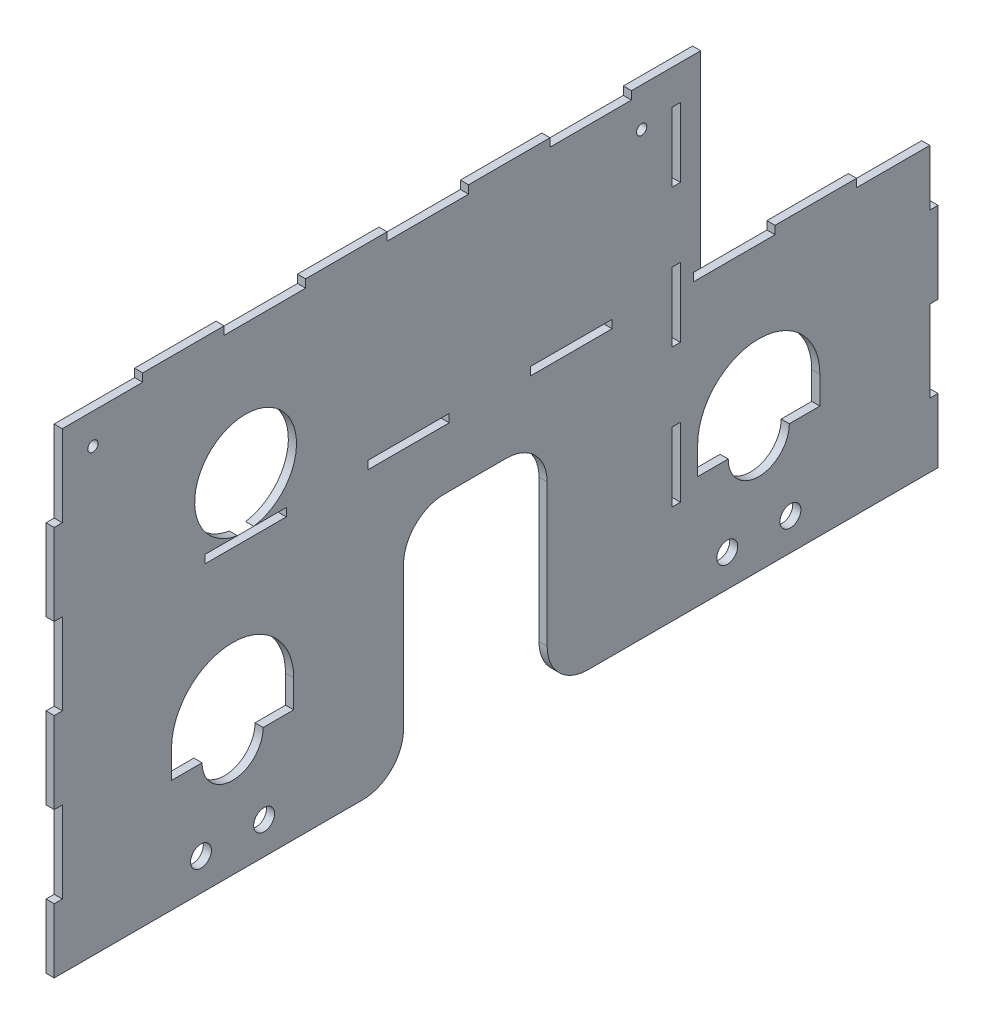
SolidWorks part; units mm, degrees
ref_plane "Front Plane" through (0, 0, 0) normal (0, 0, 1) x (1, 0, 0)
ref_plane "Top Plane" through (0, 0, 0) normal (0, 1, 0) x (1, 0, 0)
ref_plane "Right Plane" through (0, 0, 0) normal (1, 0, 0) x (0, 0, -1)
sketch "Sketch1" plane through (0, 0, 0) normal (1, 0, 0) x (0, 0, -1)
  line L1 (-112.2312, 74.803) -> (112.2312, 74.803)
  line L2 (-112.2312, 74.803) -> (-112.2312, -74.803)
  line L3 (-112.2312, -74.803) -> (112.2312, -74.803)
  line L4 (112.2312, 74.803) -> (112.2312, -74.803)
  line L5 (0, -74.803) -> (0, 74.803) construction
  line L6 (-112.2312, 0) -> (112.2312, 0) construction
  point P0 (0, 0)
  dimension "D1" = 224.4623
  dimension "D2" = 149.606
extrude "Boss-Extrude1" add sketch "Sketch1" along normal blind 2.54
sketch "Sketch2" plane through (2.54, 0, 0) normal (1, 0, 0) x (0, 0, -1)
  line L0 (-112.2312, -74.803) -> (112.2312, -74.803) construction
  line L1 (112.2312, 74.803) -> (67.7812, 74.803)
  line L2 (112.2312, 74.803) -> (112.2312, -12.7381)
  line L3 (112.2312, -12.7381) -> (67.7812, -12.7381)
  line L4 (67.7812, 74.803) -> (67.7812, -12.7381)
  dimension "D1" = 44.45
  dimension "D2" = 62.0649
extrude "Cut-Extrude1" cut sketch "Sketch2" against normal through all
fillet "Fillet1" [suppressed] radius 20.0025
hole_wizard "1/4 Clearance Hole1" positions "Sketch3" profile "Sketch5" hole size "1/4" standard "ANSI Inch"
sketch "Sketch3" plane through (2.54, 0, 0) normal (1, 0, 0) x (0, 0, -1)
  line L0 (-112.2312, -74.803) -> (112.2312, -74.803) construction
  line L3 (82.4116, -64.77) -> (102.0966, -64.77) construction
  line L6 (112.2312, -74.803) -> (112.2312, -12.7381) construction
  point P0 (-81.6978, -64.77)
  point P2 (-62.0128, -64.77)
  point P4 (102.0966, -64.77)
  point P6 (82.4116, -64.77)
  dimension "D1" = 10.033
  dimension "D2" = 19.685
  dimension "D3" = 19.685
  dimension "D4" = 144.4244
  dimension "D5" = 10.1346
sketch "Sketch5" plane through (2.54, -64.77, 81.6978) normal (0, 1, 0) x (0, 0, -1)
  line L0 (0, 0) -> (0, 11.3591)
  line L1 (0, 11.3591) -> (3.2639, 9.398)
  line L2 (3.2639, 9.398) -> (3.2639, 0)
  line L5 (3.2639, 0) -> (0, 0)
  line L10 (0, 11.3591) -> (-3.2639, 9.398) construction
  line L11 (0, -6.35) -> (0, 107.95) construction
  dimension "Hole Dia." = 6.5278
  dimension "Hole Depth" = 9.398
  dimension "Drill Angle" = 118
sketch "Sketch6" plane through (2.54, 0, 0) normal (1, 0, 0) x (0, 0, -1)
  line L0 (67.7812, 74.803) -> (-112.2312, 74.803) construction
  line L1 (52.5412, 74.803) -> (27.1412, 74.803)
  line L2 (52.5412, 74.803) -> (52.5412, 72.263)
  line L3 (52.5412, 72.263) -> (27.1412, 72.263)
  line L4 (27.1412, 74.803) -> (27.1412, 72.263)
  line L7 (67.7812, 74.803) -> (67.7812, -12.7381) construction
  dimension "D1" = 2.54
  dimension "D2" = 25.4
  dimension "D3" = 15.24
extrude "Cut-Extrude2" cut sketch "Sketch6" against normal through all
pattern_linear "LPattern1" count 4 spacing 50.8 along (0, 0, 1) of "Cut-Extrude2"
sketch "Sketch7" plane through (2.54, 0, 0) normal (1, 0, 0) x (0, 0, -1)
  line L0 (67.7812, 74.803) -> (67.7812, -12.7381) construction
  line L1 (67.7812, 64.008) -> (65.2412, 64.008)
  line L2 (67.7812, 64.008) -> (67.7812, 42.418)
  line L3 (67.7812, 42.418) -> (65.2412, 42.418)
  line L4 (65.2412, 64.008) -> (65.2412, 42.418)
  line L5 (67.7812, 74.803) -> (52.5412, 74.803) construction
  dimension "D1" = 2.54
  dimension "D2" = 21.59
  dimension "D3" = 10.795
extrude "Cut-Extrude3" cut sketch "Sketch7" against normal through all
pattern_linear "LPattern2" count 3 spacing 43.18 along (0, -1, 0) of "Cut-Extrude3"
sketch "Sketch8" plane through (2.54, 0, 0) normal (1, 0, 0) x (0, 0, -1)
  line L0 (112.2312, -74.803) -> (112.2312, -12.7381) construction
  line L1 (-112.2312, -74.803) -> (112.2312, -74.803) construction
  circle A0 centre (92.2287, -39.737) radius 9.525
  circle A1 centre (-71.8299, -39.737) radius 9.525
  dimension "D1" = 20.0025
  dimension "D2" = 35.066
  dimension "D3" = 19.05
  dimension "D4" = 164.0586
extrude "Cut-Extrude4" cut sketch "Sketch8" against normal through all
sketch "Sketch9" plane through (2.54, 0, 0) normal (1, 0, 0) x (0, 0, -1)
  line L1 (-18.5407, -74.803) -> (26.2395, -74.803)
  line L2 (-18.5407, -74.803) -> (-18.5407, -4.953)
  line L3 (-18.5407, -4.953) -> (26.2395, -4.953)
  line L4 (26.2395, -74.803) -> (26.2395, -4.953)
  line L5 (-112.2312, 72.263) -> (-112.2312, -74.803) construction
  line L6 (-112.2312, -74.803) -> (112.2312, -74.803) construction
  line L7 (-112.2312, 72.263) -> (-99.8588, 72.263) construction
  circle A0 centre (-67.7863, 31.7373) radius 15.875
  dimension "D5" = 44.4449
  dimension "D6" = 31.75
  dimension "D1" = 69.85
  dimension "D2" = 44.7802
  dimension "D3" = 93.6904
  dimension "D7" = 40.5257
extrude "Cut-Extrude5" cut sketch "Sketch9" against normal through all
fillet "Fillet2" radius 12.7 4 edges at (1.27, -4.953, -26.2395) (1.27, -4.953, 18.5407) (1.27, -74.803, -26.2395) (1.27, -74.803, 18.5407)
hole_wizard "Tap Drill for M2x0.4 Tap1" [suppressed] positions "Sketch10" profile "Sketch11" hole size "M2x0.4" standard "ANSI Metric"
sketch "Sketch10" plane through (2.54, 0, 0) normal (1, 0, 0) x (0, 0, -1)
  point P0 (-47.84, 62.1794)
  point P2 (-47.84, 13.1794)
  point P4 (10.16, 13.1794)
  point P6 (10.16, 62.1794)
  dimension "D1" = 58
  dimension "D2" = 49
  dimension "D3" = 10.16
  dimension "D4" = 13.1794
sketch "Sketch11" plane through (2.54, 62.1794, 47.84) normal (0, 1, 0) x (0, 0, -1)
  line L0 (0, 0) -> (0, 2.54)
  line L1 (0, 2.54) -> (0.8, 2.54)
  line L2 (0.8, 2.54) -> (0.8, 0)
  line L5 (0.8, 0) -> (0, 0)
  line L11 (0, -6.35) -> (0, 107.95) construction
  dimension "Thru Hole Dia." = 1.6
  dimension "Thru Hole Depth" = 2.54
sketch "Sketch12" [suppressed] plane through (2.54, 0, 0) normal (1, 0, 0) x (0, 0, -1)
  line L2 (-3.3388, -5.715) -> (60.1612, -5.715)
  line L10 (60.1612, -26.035) -> (60.1612, -5.715)
  line L12 (-3.3388, -5.715) -> (-3.3388, -26.035)
  line L14 (60.1612, -26.035) -> (-3.3388, -26.035)
  line L15 (67.7812, -0.762) -> (67.7812, -12.7381) construction
  line L16 (-112.2312, -74.803) -> (112.2312, -74.803) construction
  dimension "D1" = 7.62
  dimension "D2" = 63.5
  dimension "D3" = 48.768
  dimension "D5" = 20.32
extrude "Cut-Extrude6" [suppressed] cut sketch "Sketch12" against normal through all
fillet "Fillet3" [suppressed] radius 12.7
fillet "Fillet4" [suppressed] radius 5.08
sketch "Sketch25" plane through (2.54, 0, 0) normal (1, 0, 0) x (0, 0, -1)
  line L0 (-112.2312, -74.803) -> (-31.2407, -74.803) construction
  line L1 (-112.2312, 72.263) -> (-124.9312, 72.263)
  line L2 (-112.2312, 72.263) -> (-112.2312, -74.803)
  line L3 (-112.2312, -74.803) -> (-124.9312, -74.803)
  line L4 (-124.9312, 72.263) -> (-124.9312, -74.803)
  dimension "D1" = 12.7
extrude "Boss-Extrude5" add sketch "Sketch25" against normal blind 2.54
sketch "Sketch16" plane through (2.54, 0, 0) normal (1, 0, 0) x (0, 0, -1)
  line L1 (-124.9312, 46.863) -> (-127.4712, 46.863)
  line L2 (-124.9312, 46.863) -> (-124.9312, 21.463)
  line L3 (-124.9312, 21.463) -> (-127.4712, 21.463)
  line L4 (-127.4712, 46.863) -> (-127.4712, 21.463)
  line L5 (-124.9312, 72.263) -> (-99.8588, 72.263) construction
  line L6 (-124.9312, 72.263) -> (-124.9312, -74.803) construction
  dimension "D1" = 2.54
  dimension "D2" = 25.4
  dimension "D3" = 25.4
extrude "Boss-Extrude2" add sketch "Sketch16" against normal blind 2.54
sketch "Sketch23" plane through (2.54, 0, 0) normal (1, 0, 0) x (0, 0, -1)
  line L1 (112.2312, -12.7381) -> (67.7812, -12.7381)
  line L2 (112.2312, -12.7381) -> (112.2312, 74.803)
  line L3 (112.2312, 74.803) -> (67.7812, 74.803)
  line L4 (67.7812, -12.7381) -> (67.7812, 74.803)
extrude "Boss-Extrude3" add sketch "Sketch23" against normal blind 2.54
sketch "Sketch24" plane through (2.54, 0, 0) normal (1, 0, 0) x (0, 0, -1)
  line L0 (112.2312, 74.803) -> (52.5412, 74.803) construction
  line L1 (112.2312, -74.803) -> (145.5687, -74.803)
  line L2 (112.2312, -74.803) -> (112.2312, 74.803)
  line L3 (112.2312, 74.803) -> (145.5687, 74.803)
  line L4 (145.5687, -74.803) -> (145.5687, 74.803)
  dimension "D1" = 33.3375
extrude "Boss-Extrude4" add sketch "Sketch24" against normal blind 2.54
pattern_linear "LPattern3" count 3 spacing 50.8 along (0, -1, 0) count 2 spacing 273.0398 along (0, 0, -1) of "Boss-Extrude2"
sketch "Sketch18" plane through (2.54, 0, 0) normal (1, 0, 0) x (0, 0, -1)
  line L6 (148.1087, -80.137) -> (148.1087, -54.737) construction
  line L7 (-127.4712, -80.137) -> (148.1087, -80.137)
  line L8 (-127.4712, -80.137) -> (-127.4712, -74.803)
  line L9 (-127.4712, -74.803) -> (148.1087, -74.803)
  line L10 (148.1087, -80.137) -> (148.1087, -74.803)
  line L11 (-124.9312, -74.803) -> (-31.2407, -74.803) construction
extrude "Cut-Extrude7" cut sketch "Sketch18" against normal through all
hole_wizard "M3 Clearance Hole1" positions "Sketch13" profile "Sketch14" hole size "M3" standard "ANSI Metric"
sketch "Sketch13" plane through (2.54, 0, 0) normal (1, 0, 0) x (0, 0, -1)
  line L1 (-124.9312, 72.263) -> (-99.8588, 72.263) construction
  line L2 (65.2412, 64.008) -> (65.2412, 42.418) construction
  line L3 (27.1412, 72.263) -> (52.5412, 72.263) construction
  line L4 (-124.9312, 72.263) -> (-124.9312, 46.863) construction
  point P0 (-115.4062, 62.738)
  point P2 (55.7162, 62.738)
  dimension "D1" = 9.525
  dimension "D2" = 9.525
  dimension "D3" = 9.525
  dimension "D4" = 9.525
sketch "Sketch14" plane through (2.54, 62.738, 115.4062) normal (0, 1, 0) x (0, 0, -1)
  line L0 (0, 0) -> (0, 10.3594)
  line L1 (0, 10.3594) -> (1.6, 9.398)
  line L2 (1.6, 9.398) -> (1.6, 0)
  line L5 (1.6, 0) -> (0, 0)
  line L10 (0, 10.3594) -> (-1.6, 9.398) construction
  line L11 (0, -6.35) -> (0, 107.95) construction
  dimension "Hole Dia." = 3.2
  dimension "Hole Depth" = 9.398
  dimension "Drill Angle" = 118
hole_wizard "Tap Drill for M2x0.4 Tap2" [suppressed] positions "Sketch19" profile "Sketch20" hole size "M2x0.4" standard "ANSI Metric"
sketch "Sketch19" plane through (2.54, 0, 0) normal (1, 0, 0) x (0, 0, -1)
  point P0 (35.8912, 53.1572)
  point P2 (56.8912, 53.1572)
  point P4 (56.8912, 40.6572)
  point P6 (35.8912, 40.6572)
  dimension "D1" = 21
  dimension "D2" = 12.5
  dimension "D3" = 35.8912
  dimension "D4" = 53.1572
sketch "Sketch20" plane through (2.54, 53.1572, -35.8912) normal (0, 1, 0) x (0, 0, -1)
  line L0 (0, 0) -> (0, 2.54)
  line L1 (0, 2.54) -> (0.8, 2.54)
  line L2 (0.8, 2.54) -> (0.8, 0)
  line L5 (0.8, 0) -> (0, 0)
  line L11 (0, -6.35) -> (0, 107.95) construction
  dimension "Thru Hole Dia." = 1.6
  dimension "Thru Hole Depth" = 2.54
sketch "Sketch21" [suppressed] plane through (2.54, 0, 0) normal (1, 0, 0) x (0, 0, -1)
  circle A0 centre (46.3912, 40.6072) radius 6.985
  dimension "D1" = 46.3912
  dimension "D3" = 13.97
  dimension "D2" = 40.6072
extrude "Cut-Extrude8" [suppressed] cut sketch "Sketch21" against normal through all
ref_plane "Plane1" through (2.54, 74.803, -52.5412) normal (0, 0, 1) x (1, 0, 0)
sketch "Sketch27" plane through (2.54, 0, 0) normal (1, 0, 0) x (0, 0, -1)
  line L0 (145.5687, 74.803) -> (52.5412, 74.803) construction
  line L1 (74.1312, 74.803) -> (148.1087, 74.803)
  line L2 (74.1312, 74.803) -> (74.1312, 16.0655)
  line L3 (74.1312, 16.0655) -> (148.1087, 16.0655)
  line L4 (148.1087, 74.803) -> (148.1087, 16.0655)
  line L5 (148.1087, 21.463) -> (148.1087, 46.863) construction
  line L7 (67.7812, 64.008) -> (67.7812, 42.418) construction
  dimension "D1" = 58.7375
  dimension "D2" = 6.35
extrude "Cut-Extrude9" cut sketch "Sketch27" against normal blind 2.54
sketch "Sketch28" plane through (0, 0, 0) normal (-1, 0, 0) x (0, 0, 1)
  line L0 (-92.2287, -39.737) -> (-92.2287, -49.262) construction
  line L2 (-111.2787, -31.101) -> (-111.2787, -39.737)
  line L3 (-111.2787, -39.737) -> (-73.1787, -39.737)
  line L4 (-73.1787, -31.101) -> (-73.1787, -39.737)
  line L5 (71.8299, -39.737) -> (71.8299, -49.262) construction
  line L7 (52.7799, -31.101) -> (52.7799, -39.737)
  line L8 (52.7799, -39.737) -> (90.8799, -39.737)
  line L9 (90.8799, -31.101) -> (90.8799, -39.737)
  circle A0 centre (71.8299, -39.737) radius 9.525 construction
  circle A1 centre (-92.2287, -39.737) radius 9.525 construction
  arc A2 (-111.2787, -31.101) -> (-73.1787, -31.101) centre (-92.2287, -31.101) cw
  arc A3 (52.7799, -31.101) -> (90.8799, -31.101) centre (71.8299, -31.101) cw
  point P20 (71.8299, -39.737)
  dimension "D1" = 38.1
  dimension "D2" = 8.636
  dimension "D3" = 38.1
extrude "Cut-Extrude10" cut sketch "Sketch28" against normal blind 2.54
sketch "Sketch29" plane through (2.54, 0, 0) normal (1, 0, 0) x (0, 0, -1)
  line L0 (145.5687, -3.937) -> (145.5687, 16.0655) construction
  line L1 (148.1087, 16.0655) -> (122.7087, 16.0655)
  line L2 (148.1087, 16.0655) -> (148.1087, 13.5255)
  line L3 (148.1087, 13.5255) -> (122.7087, 13.5255)
  line L4 (122.7087, 16.0655) -> (122.7087, 13.5255)
  line L5 (74.1312, 16.0655) -> (145.5687, 16.0655) construction
  dimension "D1" = 25.4
  dimension "D2" = 2.54
  dimension "D3" = 2.54
extrude "Cut-Extrude11" cut sketch "Sketch29" against normal through all
pattern_linear "LPattern4" count 5 spacing 50.8 along (0, 0, 1) of "Cut-Extrude11"
sketch "Sketch30" [suppressed] plane through (2.54, 0, 0) normal (1, 0, 0) x (0, 0, -1)
  line L0 (-47.84, 57.0994) -> (-47.84, 22.8314) construction
  line L1 (-46.57, 57.0994) -> (-46.57, 22.8314)
  line L2 (-49.11, 57.0994) -> (-49.11, 22.8314)
  line L3 (-47.84, 62.1794) -> (-47.84, 74.803) construction
  line L4 (-23.6588, 74.803) -> (-49.0588, 74.803) construction
  arc A0 (-46.57, 57.0994) -> (-49.11, 57.0994) centre (-47.84, 57.0994) ccw
  arc A1 (-49.11, 22.8314) -> (-46.57, 22.8314) centre (-47.84, 22.8314) ccw
  circle A3 centre (-47.84, 13.1794) radius 0.8 construction
  point P2 (-47.84, 39.9654)
  dimension "D3" = 9.652
  dimension "D1" = 2.54
  dimension "D2" = 5.08
extrude "Cut-Extrude12" [suppressed] cut sketch "Sketch30" against normal through all
pattern_linear "LPattern5" [suppressed] count 22 spacing 5.08
